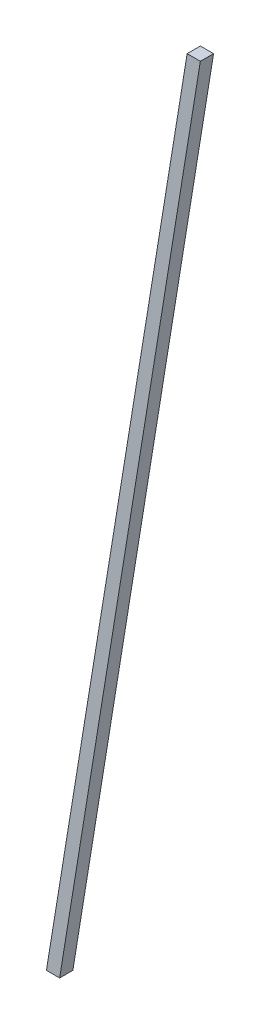
SolidWorks part; units mm, degrees
ref_plane "前视基准面" through (0, 0, 0) normal (0, 0, 1) x (1, 0, 0)
ref_plane "上视基准面" through (0, 0, 0) normal (0, 1, 0) x (1, 0, 0)
ref_plane "右视基准面" through (0, 0, 0) normal (1, 0, 0) x (0, 0, -1)
sketch "Model" plane through (0, 0, 0) normal (0, 0, 1) x (1, 0, 0)
  line L0 (72.0977, 329.5787) -> (18.8567, 2.5787)
  line L1 (72.0977, 329.5787) -> (77.0977, 329.5787)
  line L2 (77.0977, 329.5787) -> (23.8567, 2.5787)
  line L3 (18.8567, 2.5787) -> (23.8567, 2.5787)
extrude "凸台-拉伸1" add sketch "Model" along normal blind 5
